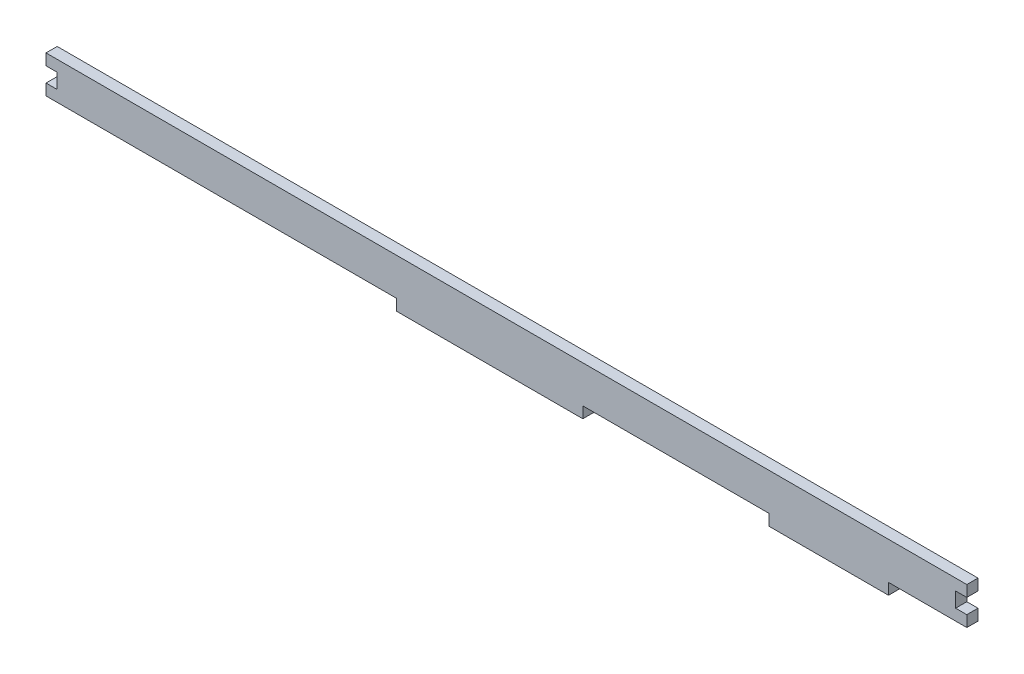
SolidWorks part; units mm, degrees
ref_plane "Front Plane" through (0, 0, 0) normal (0, 0, 1) x (1, 0, 0)
ref_plane "Top Plane" through (0, 0, 0) normal (0, 1, 0) x (1, 0, 0)
ref_plane "Right Plane" through (0, 0, 0) normal (1, 0, 0) x (0, 0, -1)
sketch "Sketch1" plane through (0, 0, 0) normal (0, 0, 1) x (1, 0, 0)
  line L0 (144, 0) -> (194, 0)
  line L1 (94, 0) -> (0, 0)
  line L2 (0, 10) -> (244, 10)
  line L3 (0, 3) -> (0, 0)
  line L4 (244, 7) -> (244, 3)
  line L5 (0, 7) -> (3, 7)
  line L6 (94, 0) -> (94, -3)
  line L7 (94, -3) -> (144, -3)
  line L8 (144, 0) -> (144, -3)
  line L9 (244, 10) -> (247, 10)
  line L10 (194, 0) -> (194, -3)
  line L11 (194, -3) -> (226, -3)
  line L12 (226, 0) -> (226, -3)
  line L14 (244, 7) -> (247, 7)
  line L15 (247, 10) -> (247, 7)
  line L16 (226, 0) -> (247, 0)
  line L18 (244, 3) -> (247, 3)
  line L19 (247, 0) -> (247, 3)
  line L22 (0, 3) -> (3, 3)
  line L23 (3, 7) -> (3, 3)
  line L25 (0, 10) -> (0, 7)
  dimension "D1" = 50
  dimension "D2" = 32
  dimension "D3" = 3
  dimension "D4" = 94
  dimension "D5" = 50
  dimension "D6" = 3
  dimension "D7" = 3
  dimension "D8" = 10
  dimension "D9" = 3
  dimension "D10" = 21
  dimension "D11" = 3
  dimension "D12" = 3
  dimension "D13" = 3
  dimension "D14" = 3
  dimension "D15" = 3
  dimension "D16" = 3
  dimension "D17" = 4
  dimension "D18" = 0
  dimension "D19" = 4
  dimension "D20" = 0
  dimension "D21" = 3
extrude "Boss-Extrude1" add sketch "Sketch1" along normal blind 3
